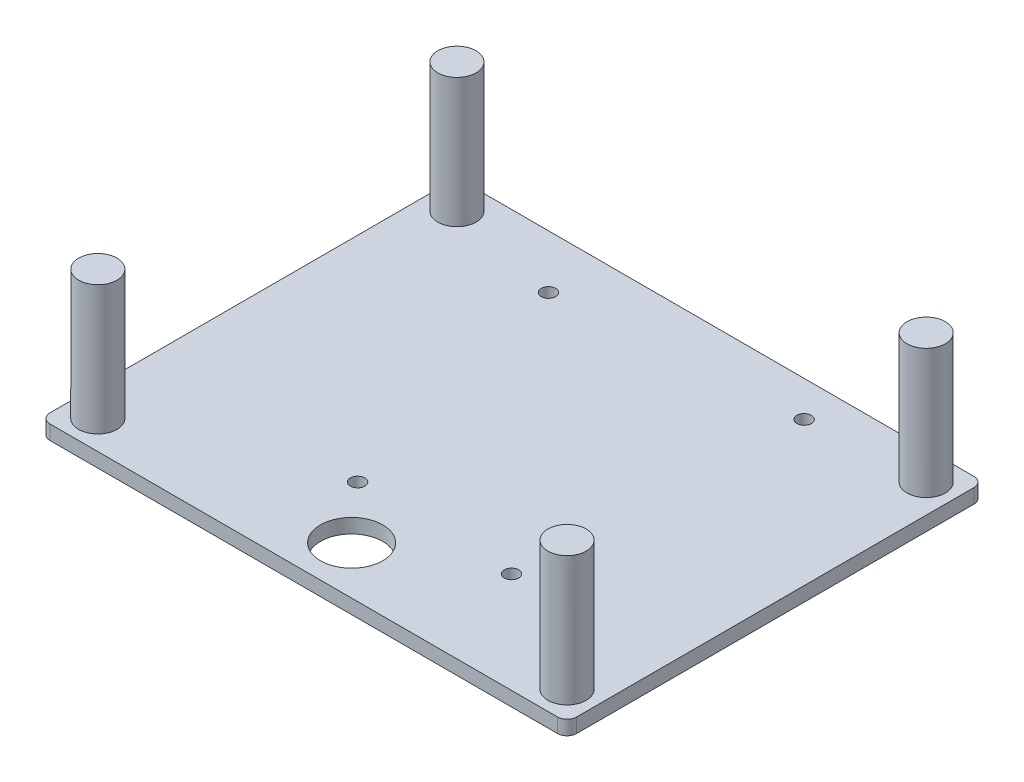
SolidWorks part; units mm, degrees
ref_plane "Ön Düzlem" through (0, 0, 0) normal (0, 0, 1) x (1, 0, 0)
ref_plane "Üst Düzlem" through (0, 0, 0) normal (0, 1, 0) x (1, 0, 0)
ref_plane "Sağ Düzlem" through (0, 0, 0) normal (1, 0, 0) x (0, 0, -1)
sketch "Çizim1" plane through (0, 0, 0) normal (0, 1, 0) x (1, 0, 0)
  line L1 (-55, -43.5) -> (55, -43.5)
  line L2 (-55, -43.5) -> (-55, 43.5)
  line L3 (-55, 43.5) -> (55, 43.5)
  line L4 (55, -43.5) -> (55, 43.5)
  line L5 (-55, -43.5) -> (55, 43.5) construction
  line L6 (-55, 43.5) -> (55, -43.5) construction
  point P0 (0, 0)
  dimension "D1" = 87
  dimension "D2" = 110
extrude "Yükseklik-Ekstrüzyon1" add sketch "Çizim1" along normal blind 3
fillet "Radyus1" radius 2 4 edges at (55, 1.5, 43.5) (55, 1.5, -43.5) (-55, 1.5, -43.5) (-55, 1.5, 43.5)
sketch "Çizim2" plane through (0, 3, 0) normal (0, 1, 0) x (1, 0, 0)
  line L0 (-55, 41.5) -> (-55, -41.5) construction
  line L1 (-53, -43.5) -> (53, -43.5) construction
  line L2 (55, -41.5) -> (55, 41.5) construction
  line L3 (53, 43.5) -> (-53, 43.5) construction
  circle A0 centre (-49, 37.5) radius 4
  circle A1 centre (49, 37.5) radius 4
  circle A2 centre (49, -37.5) radius 4
  circle A3 centre (-49, -37.5) radius 4
  dimension "D1" = 8
  dimension "D2" = 8
  dimension "D3" = 8
  dimension "D4" = 8
  dimension "D5" = 6
  dimension "D6" = 6
  dimension "D7" = 6
  dimension "D8" = 6
  dimension "D9" = 6
  dimension "D10" = 6
  dimension "D11" = 6
  dimension "D12" = 6
extrude "Yükseklik-Ekstrüzyon2" add sketch "Çizim2" along normal blind 27
sketch "Çizim4" plane through (0, 0, 0) normal (0, -1, 0) x (1, 0, 0)
  line L0 (-53, 43.5) -> (53, 43.5) construction
  circle A1 centre (0, 33.5) radius 6.5
  dimension "D1" = 13
  dimension "D2" = 10
extrude "Kes-Ekstrüzyon1" cut sketch "Çizim4" against normal blind 13
sketch "Çizim5" plane through (0, 0, 0) normal (0, -1, 0) x (-1, 0, 0)
  line L0 (55, 41.5) -> (55, -41.5) construction
  line L1 (53, -43.5) -> (-53, -43.5) construction
  line L2 (-55, -41.5) -> (-55, 41.5) construction
  line L3 (-53, 43.5) -> (53, 43.5) construction
  circle A0 centre (-22.32, -22.43) radius 1.5
  circle A1 centre (10.36, -21.88) radius 1.5
  circle A2 centre (-24.94, 36.07) radius 1.5
  circle A3 centre (24.72, 32.33) radius 1.5
  dimension "D1" = 44.64
  dimension "D3" = 3
  dimension "D4" = 3
  dimension "D7" = 30.06
  dimension "D9" = 3
  dimension "D12" = 3
  dimension "D2" = 21.62
  dimension "D5" = 21.07
  dimension "D6" = 32.68
  dimension "D8" = 7.43
  dimension "D10" = 11.17
  dimension "D11" = 30.28
extrude "Kes-Ekstrüzyon2" cut sketch "Çizim5" against normal blind 10
